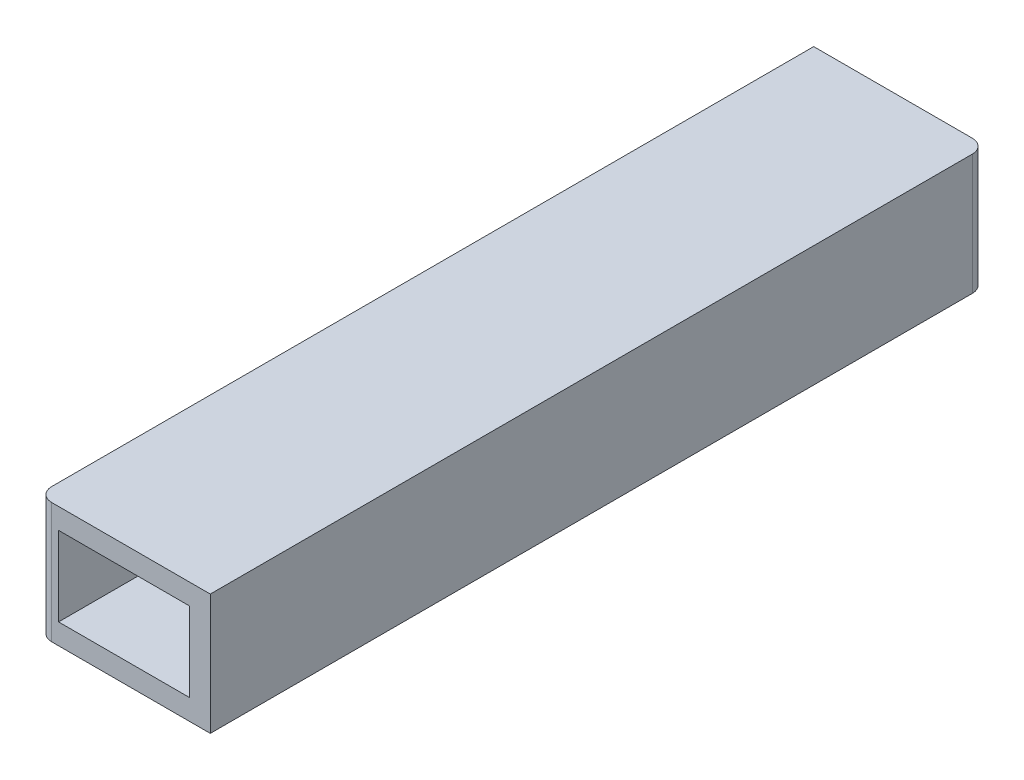
SolidWorks part; units mm, degrees
ref_plane "前视基准面" through (0, 0, 0) normal (0, 0, 1) x (1, 0, 0)
ref_plane "上视基准面" through (0, 0, 0) normal (0, 1, 0) x (1, 0, 0)
ref_plane "右视基准面" through (0, 0, 0) normal (1, 0, 0) x (0, 0, -1)
other "Configuration Table"
sketch "草图2" plane through (0, 0, 0) normal (0, 0, 1) x (1, 0, 0)
  line L1 (-50, 35) -> (50, 35)
  line L2 (-50, 35) -> (-50, -35)
  line L3 (-50, -35) -> (50, -35)
  line L4 (50, 35) -> (50, -35)
extrude "凸台-拉伸1" add sketch "草图2" along normal blind 450
sketch "草图3" plane through (0, 0, 0) normal (0, 0, -1) x (-1, 0, 0)
  line L1 (-38, 23) -> (38, 23)
  line L2 (-38, 23) -> (-38, -23)
  line L3 (-38, -23) -> (38, -23)
  line L4 (38, 23) -> (38, -23)
extrude "切除-拉伸1" cut sketch "草图3" against normal blind 420
sketch "草图4" plane through (0, 0, 450) normal (0, 0, 1) x (1, 0, 0)
  line L1 (-38, 23) -> (38, 23)
  line L2 (-38, 23) -> (-38, -23)
  line L3 (-38, -23) -> (38, -23)
  line L4 (38, 23) -> (38, -23)
extrude "切除-拉伸2" cut sketch "草图4" against normal blind 30
sketch "草图5" plane through (0, 0, 0) normal (0, 0, -1) x (-1, 0, 0)
  circle A0 centre (0, 0) radius 20
fillet "圆角1" radius 8 1 edges at (50, 0, 0)
fillet "圆角3" radius 8 1 edges at (-50, 0, 450)
